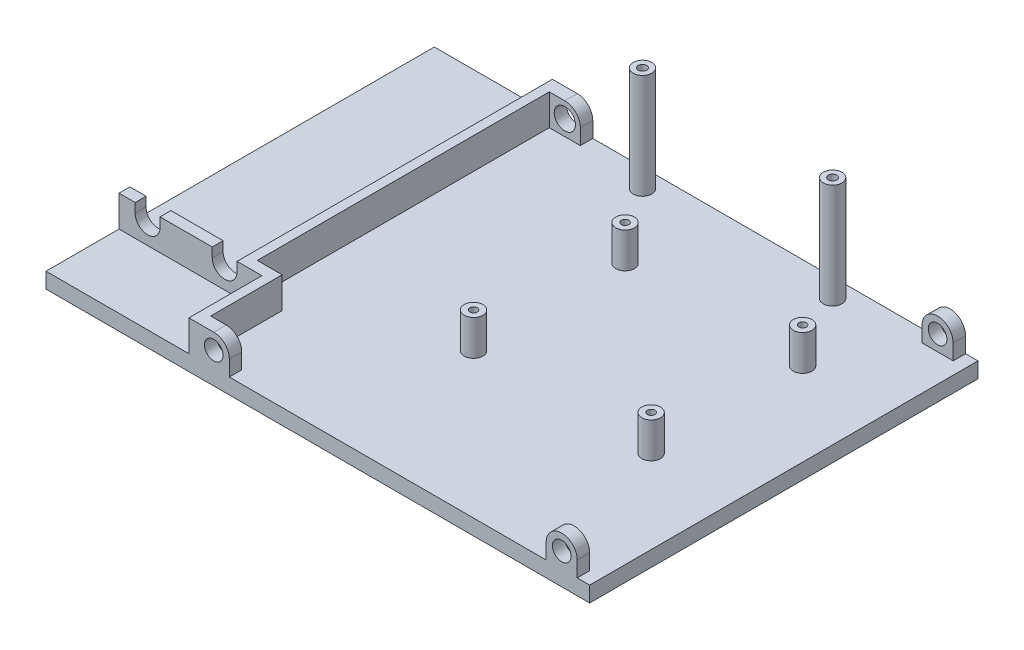
SolidWorks part; units mm, degrees
ref_plane "Front Plane" through (0, 0, 0) normal (0, 0, 1) x (1, 0, 0)
ref_plane "Top Plane" through (0, 0, 0) normal (0, 1, 0) x (1, 0, 0)
ref_plane "Right Plane" through (0, 0, 0) normal (1, 0, 0) x (0, 0, -1)
sketch "Sketch1" plane through (0, 0, 0) normal (0, 1, 0) x (1, 0, 0)
  line L1 (-87.5, 62.5) -> (87.5, 62.5)
  line L2 (-87.5, 62.5) -> (-87.5, -62.5)
  line L3 (-87.5, -62.5) -> (87.5, -62.5)
  line L4 (87.5, 62.5) -> (87.5, -62.5)
  point P4 (-87.5, 0)
  point P6 (0, 62.5)
  dimension "D1" = 125
  dimension "D2" = 175
extrude "Boss-Extrude1" add sketch "Sketch1" along normal blind 5
sketch "Sketch2" plane through (0, 5, 0) normal (0, 1, 0) x (1, 0, 0)
  line L0 (-49.5, 62.5) -> (-49.5, -35.5)
  line L1 (87.5, 62.5) -> (-87.5, 62.5) construction
  line L2 (-49.5, -35.5) -> (-87.5, -35.5)
  line L3 (-87.5, 62.5) -> (-87.5, -62.5) construction
  line L4 (-87.5, -35.5) -> (-49.5, -35.5) construction
  line L5 (-87.5, -35.5) -> (-87.5, -39)
  line L7 (-87.5, -39) -> (-41.5, -39)
  line L8 (-41.5, -39) -> (-41.5, -62.5)
  line L9 (-87.5, -62.5) -> (87.5, -62.5) construction
  line L11 (-41.5, -62.5) -> (-38.5, -62.5)
  line L12 (-38.5, -62.5) -> (-38.5, -35.5)
  line L13 (-38.5, -35.5) -> (-46.5, -35.5)
  line L14 (-46.5, -35.5) -> (-46.5, 62.5)
  line L15 (-46.5, 62.5) -> (-49.5, 62.5)
  dimension "D1" = 3
  dimension "D2" = 3
  dimension "D3" = 46
  dimension "D4" = 23.5
extrude "Boss-Extrude2" add sketch "Sketch2" along normal blind 10
sketch "Sketch3" plane through (0, 0, -62.5) normal (0, 0, -1) x (-1, 0, 0)
  line L0 (46.5, 5) -> (36.5, 5)
  line L1 (-87.5, 5) -> (46.5, 5) construction
  line L2 (36.5, 5) -> (36.5, 10)
  line L3 (38.5, 15) -> (46.5, 15) construction
  line L4 (41.5, 15) -> (46.5, 15)
  line L5 (46.5, 15) -> (46.5, 5)
  line L6 (-87.5, 148) -> (-87.5, 0) construction
  line L7 (-83.5, 10) -> (-83.5, 5)
  line L9 (-73.5, 5) -> (-73.5, 10)
  line L10 (-83.5, 5) -> (-73.5, 5)
  arc A0 (36.5, 10) -> (41.5, 15) centre (41.5, 10) cw
  circle A1 centre (41.5, 10) radius 3.41
  circle A2 centre (-78.5, 10) radius 3
  arc A3 (-73.5, 10) -> (-83.5, 10) centre (-78.5, 10) ccw
  point P12 (41.5, 5)
  dimension "D2" = 6.82
  dimension "D3" = 5
  dimension "D4" = 6
  dimension "D1" = 10
  dimension "D5" = 4
extrude "Boss-Extrude3" add sketch "Sketch3" against normal blind 4
sketch "Sketch4" plane through (0, 0, 62.5) normal (0, 0, 1) x (1, 0, 0)
  line L0 (73.5, 5) -> (83.5, 5)
  line L1 (83.5, 5) -> (83.5, 10)
  line L2 (73.5, 5) -> (73.5, 10)
  line L3 (-38.5, 15) -> (-38.5, 5)
  line L4 (-38.5, 5) -> (-28.5, 5)
  line L5 (-38.5, 5) -> (87.5, 5) construction
  line L6 (-28.5, 5) -> (-28.5, 10)
  line L7 (-38.5, 15) -> (-33.5, 15)
  arc A0 (73.5, 10) -> (83.5, 10) centre (78.5, 10) cw
  circle A1 centre (78.5, 10) radius 3
  circle A2 centre (78.5, 10) radius 3 construction
  arc A3 (-33.5, 15) -> (-28.5, 10) centre (-33.5, 10) cw
  circle A4 centre (-33.5, 10) radius 3
  point P22 (-33.5, 5)
  dimension "D2" = 6
  dimension "D1" = 10
extrude "Boss-Extrude4" add sketch "Sketch4" against normal blind 4
sketch "Sketch5" plane through (0, 5, 0) normal (0, 1, 0) x (1, 0, 0)
  line L0 (73.5, 62.5) -> (-36.5, 62.5) construction
  line L2 (-46.5, -35.5) -> (-46.5, 58.5) construction
  circle A0 centre (3.5, 32.9) radius 3
  circle A1 centre (60.65, 32.9) radius 3
  circle A2 centre (60.65, -15.868) radius 3
  circle A3 centre (3.5, -15.868) radius 3
  circle A4 centre (3.5, 32.9) radius 1.2
  circle A5 centre (60.65, 32.9) radius 1.2
  circle A6 centre (60.65, -15.868) radius 1.2
  circle A7 centre (3.5, -15.868) radius 1.2
  dimension "D1" = 6
  dimension "D2" = 2.4
  dimension "D3" = 57.15
  dimension "D4" = 48.768
  dimension "D5" = 29.6
  dimension "D6" = 50
extrude "Boss-Extrude5" add sketch "Sketch5" along normal blind 11.4
sketch "Sketch6" plane through (0, 5, 0) normal (0, 1, 0) x (1, 0, 0)
  line L0 (73.5, 62.5) -> (-36.5, 62.5) construction
  circle A0 centre (46.7, 56.5) radius 3
  circle A1 centre (-14.5, 56.5) radius 3
  circle A2 centre (46.7, 56.5) radius 1.35
  circle A3 centre (-14.5, 56.5) radius 1.35
  circle A5 centre (3.5, 32.9) radius 1.2 construction
  dimension "D1" = 6
  dimension "D2" = 2.7
  dimension "D5" = 6
  dimension "D4" = 18
  dimension "D3" = 61.2
extrude "Boss-Extrude6" add sketch "Sketch6" along normal blind 33.7
sketch "Sketch7" plane through (0, 0, 35.5) normal (0, 0, -1) x (-1, 0, 0)
  line L0 (49.5, 15) -> (49.5, 12)
  line L1 (49.5, 15) -> (49.5, 5) construction
  line L2 (49.5, 15) -> (57.5, 15)
  line L3 (49.5, 15) -> (87.5, 15) construction
  line L4 (57.5, 15) -> (57.5, 12)
  line L5 (65.9, 18.2618) -> (65.9, 8.6755) construction
  line L6 (74.3, 15) -> (74.3, 12)
  line L7 (82.3, 15) -> (74.3, 15)
  line L8 (82.3, 15) -> (82.3, 12)
  arc A0 (49.5, 12) -> (57.5, 12) centre (53.5, 12) ccw
  arc A1 (82.3, 12) -> (74.3, 12) centre (78.3, 12) cw
  dimension "D1" = 8.4
  dimension "D2" = 8
  dimension "D3" = 3
extrude "Cut-Extrude1" cut sketch "Sketch7" against normal up to next
equation "\"Printed Hole Size\"= 6.5"
equation "\"CAD Hole Size\"= 0.9683 * \"Printed Hole Size\" + 0.5265"
